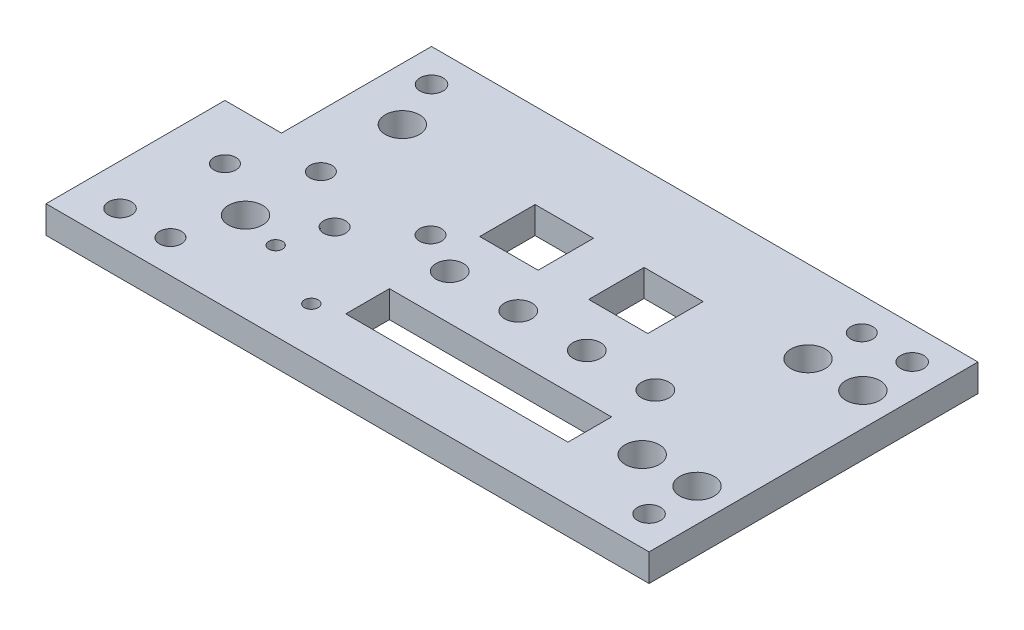
SolidWorks part; units mm, degrees
material "K110"
ref_plane "Front Plane" through (0, 0, 0) normal (0, 0, 1) x (1, 0, 0)
ref_plane "Top Plane" through (0, 0, 0) normal (0, 1, 0) x (1, 0, 0)
ref_plane "Right Plane" through (0, 0, 0) normal (1, 0, 0) x (0, 0, -1)
sketch "Sketch1" plane through (0, 0, 0) normal (0, 1, 0) x (1, 0, 0)
  line L1 (-110, -60) -> (110, -60)
  line L2 (-110, -60) -> (-110, 60)
  line L3 (-110, 60) -> (110, 60)
  line L4 (110, -60) -> (110, 60)
  line L5 (-110, -60) -> (110, 60) construction
  line L6 (-110, 60) -> (110, -60) construction
  point P0 (0, 0)
  dimension "D1" = 120
  dimension "D2" = 220
extrude "Boss-Extrude1" add sketch "Sketch1" against normal blind 10
sketch "Sketch2" plane through (0, 0, 0) normal (0, 1, 0) x (1, 0, 0)
  line L1 (-110, 60) -> (-89.3675, 60)
  line L2 (-110, 60) -> (-110, 5.27)
  line L3 (-110, 5.27) -> (-89.3675, 5.27)
  line L4 (-89.3675, 60) -> (-89.3675, 5.27)
  line L5 (-90, -14.72) -> (-89.3675, 5.27) construction
  line L10 (-70, 0.28) -> (-89.3675, 5.27) construction
  dimension "D1" = 20
extrude "Cut-Extrude1" cut sketch "Sketch2" against normal up to next
hole_wizard "Ø12.5 (12.5) Diameter Hole1" positions "Sketch5" profile "Sketch4" hole size "Ø12.5" standard "ISO" end condition through all
sketch "Sketch5" plane through (0, -10, 0) normal (0, -1, 0) x (-1, 0, 0)
  point P0 (-98, 30)
  point P3 (-78, 30)
  point P6 (70, 30)
  point P9 (-98, -30.5)
  point P12 (-78, -30.5)
  point P15 (70, -27.22)
sketch "Sketch4" plane through (98, -10, -30) normal (1, 0, 0) x (0, 0, -1)
  line L0 (0, 0) -> (0, 10)
  line L1 (0, 10) -> (6.25, 10)
  line L2 (6.25, 10) -> (6.25, 0)
  line L5 (6.25, 0) -> (0, 0)
  line L11 (0, -6.35) -> (0, 107.95) construction
  dimension "Thru Hole Dia." = 12.5
  dimension "Thru Hole Depth" = 10
hole_wizard "Ø10.0 (10) Diameter Hole1" positions "Sketch8" profile "Sketch7" hole size "Ø10.0" standard "ISO" end condition through all
sketch "Sketch8" plane through (0, -10, 0) normal (0, -1, 0) x (-1, 0, 0)
  point P0 (-60, -7.72)
  point P3 (-35, -7.72)
  point P6 (-10, -7.72)
  point P9 (15, -7.72)
sketch "Sketch7" plane through (60, -10, 7.72) normal (1, 0, 0) x (0, 0, -1)
  line L0 (0, 0) -> (0, 10)
  line L1 (0, 10) -> (5, 10)
  line L2 (5, 10) -> (5, 0)
  line L5 (5, 0) -> (0, 0)
  line L11 (0, -6.35) -> (0, 107.95) construction
  dimension "Thru Hole Dia." = 10
  dimension "Thru Hole Depth" = 10
hole_wizard "Ø5.0mm Dowel Hole1" positions "Sketch11" profile "Sketch10" hole size "Ø5.0" standard "ISO" end condition through all
sketch "Sketch11" plane through (0, -10, 0) normal (0, -1, 0) x (-1, 0, 0)
  point P0 (30, -43.22)
  point P3 (55, -31.22)
sketch "Sketch10" plane through (-30, -10, 43.22) normal (1, 0, 0) x (0, 0, -1)
  line L0 (0, 0) -> (0, 10)
  line L1 (0, 10) -> (2.5, 10)
  line L2 (2.5, 10) -> (2.5, 0)
  line L5 (2.5, 0) -> (0, 0)
  line L11 (0, -6.35) -> (0, 107.95) construction
  dimension "Thru Hole Dia." = 5
  dimension "Thru Hole Depth" = 10
sketch "Sketch12" plane through (0, -10, 0) normal (0, -1, 0) x (1, 0, 0)
  line L674 (60.5278, 40.1278) -> (60.5278, 24.1922) construction
  line L675 (60.5278, 24.1922) -> (-20.5278, 24.1922) construction
  line L676 (-20.5278, 40.1278) -> (60.5278, 40.1278) construction
  line L677 (-20.5278, 24.1922) -> (-20.5278, 40.1278) construction
  line L678 (60.5278, 40.1278) -> (60.5278, 24.1922)
  line L679 (60.5278, 24.1922) -> (-20.5278, 24.1922)
  line L680 (-20.5278, 40.1278) -> (60.5278, 40.1278)
  line L681 (-20.5278, 24.1922) -> (-20.5278, 40.1278)
  line L682 (-20.5278, -8.7522) -> (0.7778, -8.7522) construction
  line L683 (-20.5278, -28.9678) -> (-20.5278, -8.7522) construction
  line L684 (0.7778, -28.9678) -> (-20.5278, -28.9678) construction
  line L685 (0.7778, -8.7522) -> (0.7778, -28.9678) construction
  line L686 (19.2222, -28.9678) -> (19.2222, -8.7522) construction
  line L687 (40.7778, -28.9678) -> (19.2222, -28.9678) construction
  line L688 (40.7778, -8.7522) -> (40.7778, -28.9678) construction
  line L689 (19.2222, -8.7522) -> (40.7778, -8.7522) construction
  line L690 (-20.5278, -8.7522) -> (0.7778, -8.7522)
  line L691 (-20.5278, -28.9678) -> (-20.5278, -8.7522)
  line L692 (0.7778, -28.9678) -> (-20.5278, -28.9678)
  line L693 (0.7778, -8.7522) -> (0.7778, -28.9678)
  line L694 (19.2222, -28.9678) -> (19.2222, -8.7522)
  line L695 (40.7778, -28.9678) -> (19.2222, -28.9678)
  line L696 (40.7778, -8.7522) -> (40.7778, -28.9678)
  line L697 (19.2222, -8.7522) -> (40.7778, -8.7522)
  circle A0 centre (-90, 14.72) radius 4 construction
  circle A1 centre (-70, -0.28) radius 4 construction
  circle A2 centre (-50, 14.72) radius 4 construction
  circle A3 centre (-30, -0.28) radius 4 construction
  circle A4 centre (-90, 14.72) radius 4
  circle A5 centre (-70, -0.28) radius 4
  circle A6 centre (-50, 14.72) radius 4
  circle A7 centre (-30, -0.28) radius 4
extrude "Cut-Extrude2" cut sketch "Sketch12" against normal up to next
draft "Draft1" type of draft neutral plane draft angle 1 faces to draft 16 face at (60.5278, -5, 32.16) face at (20, -5, 40.1278) face at (-20.5278, -5, 32.16) face at (20, -5, 24.1922) face at (-9.875, -5, -8.7522) face at (30, -5, -8.7522) face at (40.7778, -5, -18.86) face at (0.7778, -5, -18.86) face at (-20.5278, -5, -18.86) face at (19.2222, -5, -18.86) face at (30, -5, -28.9678) face at (-9.875, -5, -28.9678) face at (-50, -10, 10.72) face at (-30, -10, -4.28) face at (-70, -10, -4.28) face at (-90, -10, 10.72) neutral plane through (0, 0, 0) neutral plane normal (0, 1, 0) reverse direction yes parameters "D1"=1
hole_wizard "Ø8.0mm Dowel Hole1" positions "Sketch16" profile "Sketch14" hole size "Ø8.0" standard "ISO" end condition through all
sketch "Sketch16" plane through (0, -10, 0) normal (0, -1, 0) x (-1, 0, 0)
  point P9 (76.6, -48)
  point P12 (-79.6, 48)
sketch "Sketch14" plane through (-76.6, -10, 48) normal (1, 0, 0) x (0, 0, -1)
  line L0 (0, 0) -> (0, 10)
  line L1 (0, 10) -> (4, 10)
  line L2 (4, 10) -> (4, 0)
  line L5 (4, 0) -> (0, 0)
  line L11 (0, -6.35) -> (0, 107.95) construction
  dimension "Thru Hole Dia." = 8
  dimension "Thru Hole Depth" = 10
hole_wizard "M8 Clearance Hole1" positions "Sketch21" profile "Sketch20" hole size "M8" standard "ISO" end condition through all
sketch "Sketch21" plane through (0, 0, 0) normal (0, 1, 0) x (1, 0, 0)
  point P0 (-95, -48)
  point P3 (98, -48)
  point P6 (98, 48)
  point P9 (-77.3675, 48)
sketch "Sketch20" plane through (-95, 0, 48) normal (1, 0, 0) x (0, 0, 1)
  line L0 (0, 0) -> (0, 10)
  line L1 (0, 10) -> (4.2, 10)
  line L2 (4.2, 10) -> (4.2, 0)
  line L5 (4.2, 0) -> (0, 0)
  line L11 (0, -6.35) -> (0, 107.95) construction
  dimension "Thru Hole Dia." = 8.4
  dimension "Thru Hole Depth" = 10
